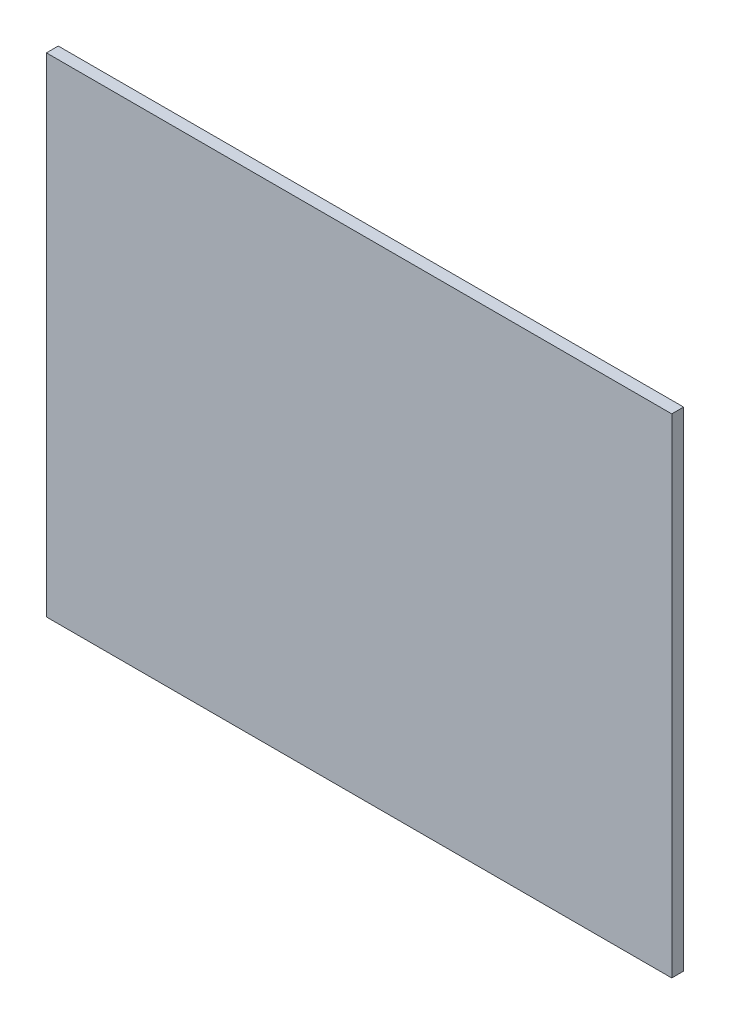
SolidWorks part; units mm, degrees
ref_plane "Front Plane" through (0, 0, 0) normal (0, 0, 1) x (1, 0, 0)
ref_plane "Top Plane" through (0, 0, 0) normal (0, 1, 0) x (1, 0, 0)
ref_plane "Right Plane" through (0, 0, 0) normal (1, 0, 0) x (0, 0, -1)
sketch "Sketch1" plane through (0, 0, 0) normal (1, 0, 0) x (0, 0, -1)
  line L1 (-7.6919, -317.5) -> (7.6919, -317.5)
  line L2 (-7.6919, -317.5) -> (-7.6919, 317.5)
  line L3 (-7.6919, 317.5) -> (7.6919, 317.5)
  line L4 (7.6919, -317.5) -> (7.6919, 317.5)
  line L5 (-7.6919, -317.5) -> (7.6919, 317.5) construction
  line L6 (-7.6919, 317.5) -> (7.6919, -317.5) construction
  point P0 (0, 0)
  dimension "D1" = 635
extrude "Boss-Extrude1" add sketch "Sketch1" along normal blind 812.8
